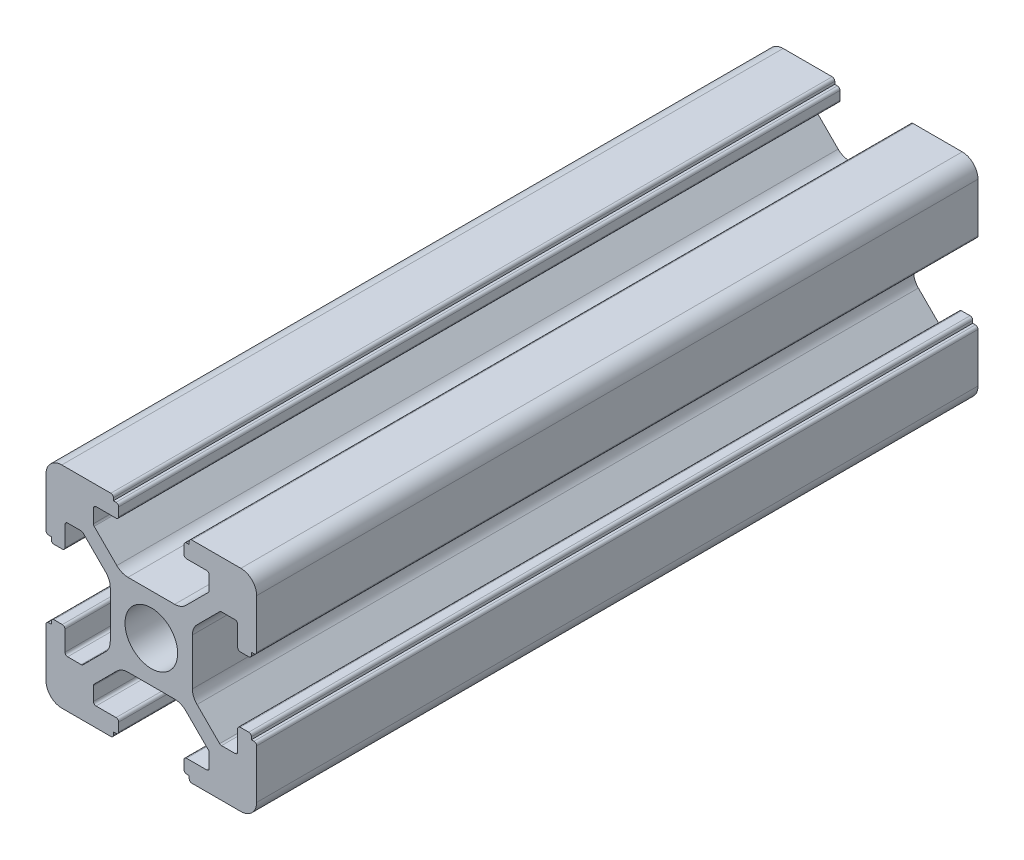
SolidWorks part; units mm, degrees
ref_plane "前视基准面" through (0, 0, 0) normal (0, 0, 1) x (1, 0, 0)
ref_plane "上视基准面" through (0, 0, 0) normal (0, 1, 0) x (1, 0, 0)
ref_plane "右视基准面" through (0, 0, 0) normal (1, 0, 0) x (0, 0, -1)
sketch "草图1" plane through (0, 0, 0) normal (0, 0, 1) x (1, 0, 0)
  line L0 (0, 0) -> (0, 5.5) construction
  line L1 (-8.5023, -10.0023) -> (-3.85, -10.0023)
  line L2 (-10.0023, -8.5023) -> (-10.0023, -3.85)
  line L3 (-8.5023, 10.0023) -> (-3.85, 10.0023)
  line L4 (10.0023, -8.5023) -> (10.0023, -3.85)
  line L5 (-10.0023, -10.0023) -> (10.0023, 10.0023) construction
  line L6 (-10.0023, 10.0023) -> (10.0023, -10.0023) construction
  line L7 (-2.218, -3.9) -> (2.218, -3.9)
  line L8 (-3.9, -2.218) -> (-3.9, 2.218)
  line L9 (-2.218, 3.9) -> (2.218, 3.9)
  line L10 (3.9, -2.218) -> (3.9, 2.218)
  line L11 (-3.9, -3.9) -> (3.9, 3.9) construction
  line L12 (-3.9, 3.9) -> (3.9, -3.9) construction
  line L13 (-5.25, -8.2) -> (-3.35, -8.2)
  line L14 (-8.2, -5.25) -> (-8.2, -3.35)
  line L15 (-5.25, 8.2) -> (-3.35, 8.2)
  line L16 (8.2, -5.25) -> (8.2, -3.35)
  line L17 (-8.2, -8.2) -> (8.2, 8.2) construction
  line L18 (-8.2, 8.2) -> (8.2, -8.2) construction
  line L19 (-7.95, 5.5) -> (-6.6642, 5.5)
  line L20 (0, 0) -> (5.5, 0) construction
  line L23 (-5.5, 7.95) -> (-5.5, 6.6642)
  line L26 (0, 0) -> (-0.5303, 0.5303)
  line L27 (3.2787, 4.3393) -> (5.4268, 6.4874)
  line L28 (0, 0) -> (0.5303, -0.5303)
  line L29 (5.5, 6.6642) -> (5.5, 7.95)
  line L30 (4.3393, 3.2787) -> (6.4874, 5.4268)
  line L31 (6.6642, 5.5) -> (7.95, 5.5)
  line L32 (4.3393, -3.2787) -> (6.4874, -5.4268)
  line L33 (3.2787, -4.3393) -> (5.4268, -6.4874)
  line L34 (-3.2787, -4.3393) -> (-5.4268, -6.4874)
  line L35 (-4.3393, -3.2787) -> (-6.4874, -5.4268)
  line L36 (-4.3393, 3.2787) -> (-6.4874, 5.4268)
  line L37 (-3.2787, 4.3393) -> (-5.4268, 6.4874)
  line L38 (3.1, -8.45) -> (3.1, -9.2523)
  line L39 (8.45, 3.1) -> (9.2523, 3.1)
  line L40 (-5.5, -6.6642) -> (-5.5, -7.95)
  line L41 (-6.6642, -5.5) -> (-7.95, -5.5)
  line L42 (5.5, -6.6642) -> (5.5, -7.95)
  line L43 (6.6642, -5.5) -> (7.95, -5.5)
  line L44 (9.2523, -3.1) -> (8.45, -3.1)
  line L46 (10.0023, 3.85) -> (10.0023, 8.5023)
  line L47 (8.2, 3.35) -> (8.2, 5.25)
  line L48 (-3.1, -9.2523) -> (-3.1, -8.45)
  line L49 (-8.45, -3.1) -> (-9.2523, -3.1)
  line L50 (-9.2523, 3.1) -> (-8.45, 3.1)
  line L51 (-3.1, 8.45) -> (-3.1, 9.2523)
  line L52 (3.1, 9.2523) -> (3.1, 8.45)
  line L53 (3.85, 10.0023) -> (8.5023, 10.0023)
  line L54 (3.35, 8.2) -> (5.25, 8.2)
  line L55 (-10.0023, 3.85) -> (-10.0023, 8.5023)
  line L56 (-8.2, 3.35) -> (-8.2, 5.25)
  line L57 (3.35, -8.2) -> (5.25, -8.2)
  line L58 (3.85, -10.0023) -> (8.5023, -10.0023)
  line L59 (9.7523, -3.6) -> (9.5023, -3.6)
  line L61 (9.7523, 3.6) -> (9.5023, 3.6)
  line L62 (9.5023, -3.6) -> (9.5023, -3.35)
  line L63 (3.6, -9.7523) -> (3.6, -9.5023)
  line L64 (3.35, -9.5023) -> (3.6, -9.5023)
  line L65 (9.5023, 3.35) -> (9.5023, 3.6)
  line L66 (-3.6, -9.5023) -> (-3.35, -9.5023)
  line L67 (-3.6, -9.7523) -> (-3.6, -9.5023)
  line L68 (-9.7523, -3.6) -> (-9.5023, -3.6)
  line L69 (-9.5023, -3.35) -> (-9.5023, -3.6)
  line L70 (-9.5023, 3.6) -> (-9.5023, 3.35)
  line L71 (-9.7523, 3.6) -> (-9.5023, 3.6)
  line L72 (-3.6, 9.7523) -> (-3.6, 9.5023)
  line L73 (-3.35, 9.5023) -> (-3.6, 9.5023)
  line L74 (3.6, 9.5023) -> (3.35, 9.5023)
  line L75 (3.6, 9.7523) -> (3.6, 9.5023)
  circle A0 centre (0, 0) radius 2.5
  arc A1 (10.0023, 8.5023) -> (8.5023, 10.0023) centre (8.5023, 8.5023) ccw
  arc A2 (8.5023, -10.0023) -> (10.0023, -8.5023) centre (8.5023, -8.5023) ccw
  arc A3 (-10.0023, -8.5023) -> (-8.5023, -10.0023) centre (-8.5023, -8.5023) ccw
  arc A4 (-10.0023, 8.5023) -> (-8.5023, 10.0023) centre (-8.5023, 8.5023) cw
  arc A5 (-9.5023, -3.35) -> (-9.2523, -3.1) centre (-9.2523, -3.35) cw
  arc A6 (-9.7523, -3.6) -> (-10.0023, -3.85) centre (-9.7523, -3.85) ccw
  arc A7 (-8.45, -3.1) -> (-8.2, -3.35) centre (-8.45, -3.35) cw
  arc A8 (-7.95, -5.5) -> (-8.2, -5.25) centre (-7.95, -5.25) cw
  arc A9 (-6.4874, -5.4268) -> (-6.6642, -5.5) centre (-6.6642, -5.25) cw
  arc A10 (-5.4268, -6.4874) -> (-5.5, -6.6642) centre (-5.25, -6.6642) ccw
  arc A11 (-5.5, -7.95) -> (-5.25, -8.2) centre (-5.25, -7.95) ccw
  arc A12 (-3.6, -9.7523) -> (-3.85, -10.0023) centre (-3.85, -9.7523) cw
  arc A13 (-3.35, -9.5023) -> (-3.1, -9.2523) centre (-3.35, -9.2523) ccw
  arc A14 (-3.1, -8.45) -> (-3.35, -8.2) centre (-3.35, -8.45) ccw
  arc A15 (3.1, -8.45) -> (3.35, -8.2) centre (3.35, -8.45) cw
  arc A16 (5.5, -7.95) -> (5.25, -8.2) centre (5.25, -7.95) cw
  arc A17 (5.4268, -6.4874) -> (5.5, -6.6642) centre (5.25, -6.6642) cw
  arc A18 (6.4874, -5.4268) -> (6.6642, -5.5) centre (6.6642, -5.25) ccw
  arc A19 (7.95, -5.5) -> (8.2, -5.25) centre (7.95, -5.25) ccw
  arc A20 (8.45, -3.1) -> (8.2, -3.35) centre (8.45, -3.35) ccw
  arc A21 (9.5023, -3.35) -> (9.2523, -3.1) centre (9.2523, -3.35) ccw
  arc A22 (9.7523, -3.6) -> (10.0023, -3.85) centre (9.7523, -3.85) cw
  arc A23 (3.35, -9.5023) -> (3.1, -9.2523) centre (3.35, -9.2523) cw
  arc A24 (3.6, -9.7523) -> (3.85, -10.0023) centre (3.85, -9.7523) ccw
  arc A25 (7.95, 5.5) -> (8.2, 5.25) centre (7.95, 5.25) cw
  arc A26 (8.2, 3.35) -> (8.45, 3.1) centre (8.45, 3.35) ccw
  arc A27 (9.5023, 3.35) -> (9.2523, 3.1) centre (9.2523, 3.35) cw
  arc A28 (9.7523, 3.6) -> (10.0023, 3.85) centre (9.7523, 3.85) ccw
  arc A29 (6.6642, 5.5) -> (6.4874, 5.4268) centre (6.6642, 5.25) ccw
  arc A30 (5.4268, 6.4874) -> (5.5, 6.6642) centre (5.25, 6.6642) ccw
  arc A31 (5.5, 7.95) -> (5.25, 8.2) centre (5.25, 7.95) ccw
  arc A32 (3.1, 8.45) -> (3.35, 8.2) centre (3.35, 8.45) ccw
  arc A33 (3.6, 9.7523) -> (3.85, 10.0023) centre (3.85, 9.7523) cw
  arc A34 (3.35, 9.5023) -> (3.1, 9.2523) centre (3.35, 9.2523) ccw
  arc A35 (-9.7523, 3.6) -> (-10.0023, 3.85) centre (-9.7523, 3.85) cw
  arc A36 (-9.5023, 3.35) -> (-9.2523, 3.1) centre (-9.2523, 3.35) ccw
  arc A37 (-8.45, 3.1) -> (-8.2, 3.35) centre (-8.45, 3.35) ccw
  arc A38 (-8.2, 5.25) -> (-7.95, 5.5) centre (-7.95, 5.25) cw
  arc A39 (-6.4874, 5.4268) -> (-6.6642, 5.5) centre (-6.6642, 5.25) ccw
  arc A40 (-5.4268, 6.4874) -> (-5.5, 6.6642) centre (-5.25, 6.6642) cw
  arc A41 (-5.5, 7.95) -> (-5.25, 8.2) centre (-5.25, 7.95) cw
  arc A42 (-3.1, 8.45) -> (-3.35, 8.2) centre (-3.35, 8.45) cw
  arc A43 (-3.1, 9.2523) -> (-3.35, 9.5023) centre (-3.35, 9.2523) ccw
  arc A44 (-3.6, 9.7523) -> (-3.85, 10.0023) centre (-3.85, 9.7523) ccw
  arc A45 (-4.3393, 3.2787) -> (-3.9, 2.218) centre (-5.4, 2.218) cw
  arc A46 (-3.2787, 4.3393) -> (-2.218, 3.9) centre (-2.218, 5.4) ccw
  arc A47 (3.2787, 4.3393) -> (2.218, 3.9) centre (2.218, 5.4) cw
  arc A48 (4.3393, 3.2787) -> (3.9, 2.218) centre (5.4, 2.218) ccw
  arc A49 (4.3393, -3.2787) -> (3.9, -2.218) centre (5.4, -2.218) cw
  arc A50 (3.2787, -4.3393) -> (2.218, -3.9) centre (2.218, -5.4) ccw
  arc A51 (-4.3393, -3.2787) -> (-3.9, -2.218) centre (-5.4, -2.218) ccw
  arc A52 (-2.218, -3.9) -> (-3.2787, -4.3393) centre (-2.218, -5.4) ccw
  point P0 (0, 0)
  point P7 (10.0023, 0)
  point P62 (0, 0)
  point P76 (0, 0)
  point P92 (-8.2, -5.5)
  point P99 (0, 0)
  point P106 (-5.5, -8.2)
  point P117 (5.5, -8.2)
  point P124 (8.2, -5.5)
  point P137 (8.2, 5.5)
  point P140 (8.2, 3.1)
  point P147 (6.5607, 5.5)
  point P152 (5.5, 8.2)
  point P167 (-8.2, 5.5)
  point P174 (-5.5, 8.2)
  dimension "D1" = 1.5
  dimension "D5" = 0.25
  dimension "D6" = 1.5
  dimension "D2" = 4
  dimension "D3" = 4
  dimension "D4" = 4
extrude "凸台-拉伸1" add sketch "草图1" along normal blind 68.5 contours A52 L7 A50 L33 A17 L42 A16 L57 A15 L38 A23 L64 L63 A24 L58 A2 L4 A22 L59 L62 A21 L44 A20 L16 A19 L43 A18 L32 A49 L10 A48 L30 A29 L31 A25 L47 A26 L39 A27 L65 L61 A28 L46 A1 L53 A33 L75 L74 A34 L52 A32
